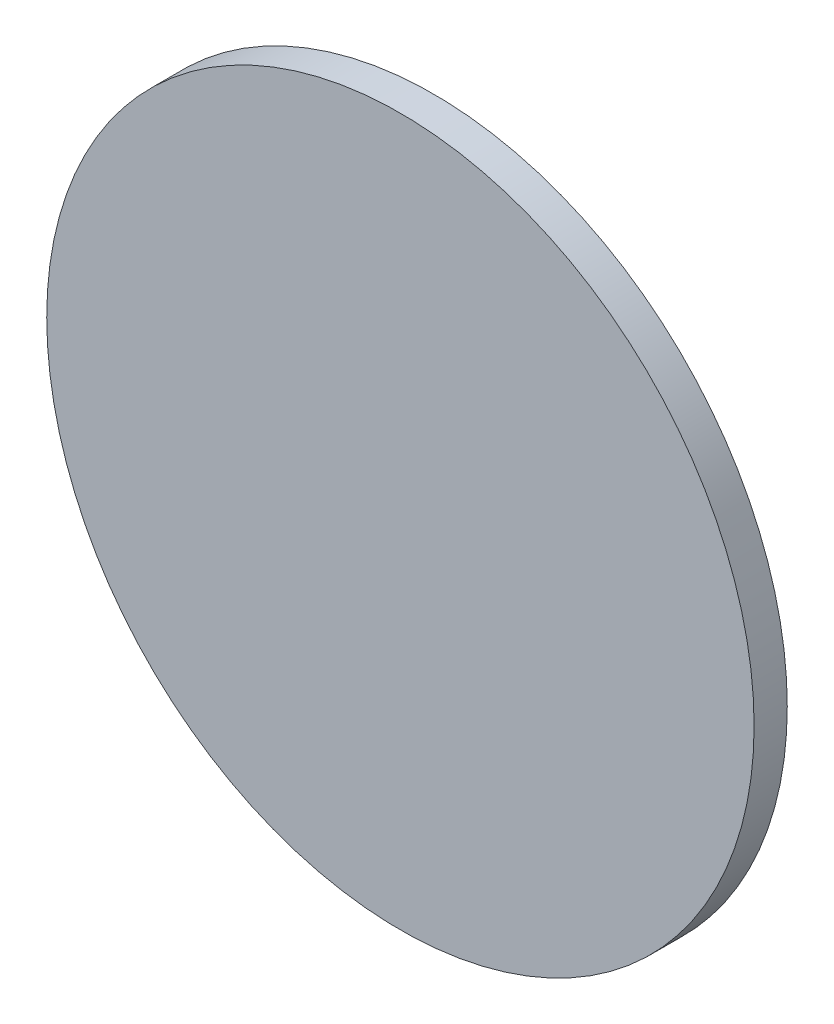
SolidWorks part; units mm, degrees
ref_plane "Front Plane" through (0, 0, 0) normal (0, 0, 1) x (1, 0, 0)
ref_plane "Top Plane" through (0, 0, 0) normal (0, 1, 0) x (1, 0, 0)
ref_plane "Right Plane" through (0, 0, 0) normal (1, 0, 0) x (0, 0, -1)
sketch "Sketch1" plane through (0, 0, 0) normal (0, 0, 1) x (1, 0, 0)
  circle A0 centre (0, 0) radius 203.2
  dimension "D1" = 406.4
extrude "Boss-Extrude1" add sketch "Sketch1" along normal blind 19.05 contours A0
equation "\"prop_diameter\"=16"
equation "\"D1@Sketch1\"=\"prop_diameter\""
equation "\"prop_depth\"=0.75"
equation "\"D1@Boss-Extrude1\"=\"prop_depth\""
